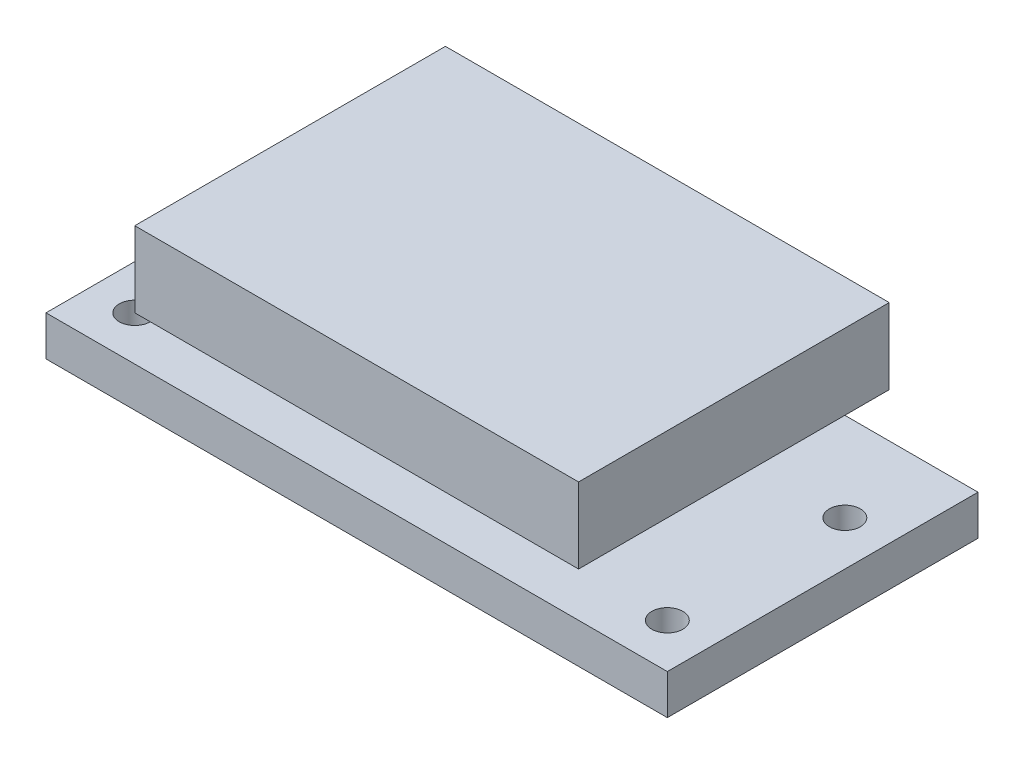
SolidWorks part; units mm, degrees
ref_plane "Front Plane" through (0, 0, 0) normal (0, 0, 1) x (1, 0, 0)
ref_plane "Top Plane" through (0, 0, 0) normal (0, 1, 0) x (1, 0, 0)
ref_plane "Right Plane" through (0, 0, 0) normal (1, 0, 0) x (0, 0, -1)
sketch "Sketch1" plane through (0, 0, 0) normal (0, 1, 0) x (1, 0, 0)
  line L0 (-4.8579, 7.5) -> (49995.1421, 7.5) construction
  line L1 (-35, 17.5) -> (35, 17.5)
  line L2 (-35, 17.5) -> (-35, -17.5)
  line L3 (-35, -17.5) -> (35, -17.5)
  line L4 (35, 17.5) -> (35, -17.5)
  line L5 (-35, 17.5) -> (35, -17.5) construction
  line L6 (-35, -17.5) -> (35, 17.5) construction
  line L7 (-8.4281, -12.5) -> (49991.5719, -12.5) construction
  line L8 (30, -1.3462) -> (30, -50001.3462) construction
  line L9 (-30, -0.4097) -> (-30, -50000.4097) construction
  circle A0 centre (-30, 7.5) radius 1.75
  circle A1 centre (30, 7.5) radius 1.75
  circle A2 centre (30, -12.5) radius 1.75
  circle A3 centre (-30, -12.5) radius 1.75
  point P0 (0, 0)
  dimension "D7" = 3.5
  dimension "D1" = 35
  dimension "D2" = 70
  dimension "D3" = 10
  dimension "D4" = 5
  dimension "D5" = 5
  dimension "D6" = 5
extrude "Boss-Extrude1" add sketch "Sketch1" along normal blind 4.5
ref_plane "Plane1" through (0, 9.5, 0) normal (0, 1, 0) x (1, 0, 0)
sketch "Sketch2" plane through (0, 9.5, 0) normal (0, 1, 0) x (1, 0, 0)
  line L1 (-25, 17.5) -> (25, 17.5)
  line L2 (-25, 17.5) -> (-25, -17.5)
  line L3 (-25, -17.5) -> (25, -17.5)
  line L4 (25, 17.5) -> (25, -17.5)
  line L5 (-25, 17.5) -> (25, -17.5) construction
  line L6 (-25, -17.5) -> (25, 17.5) construction
  point P0 (0, 0)
  dimension "D1" = 35
  dimension "D2" = 50
extrude "Boss-Extrude2" add sketch "Sketch2" along normal blind 8.5 separate body
